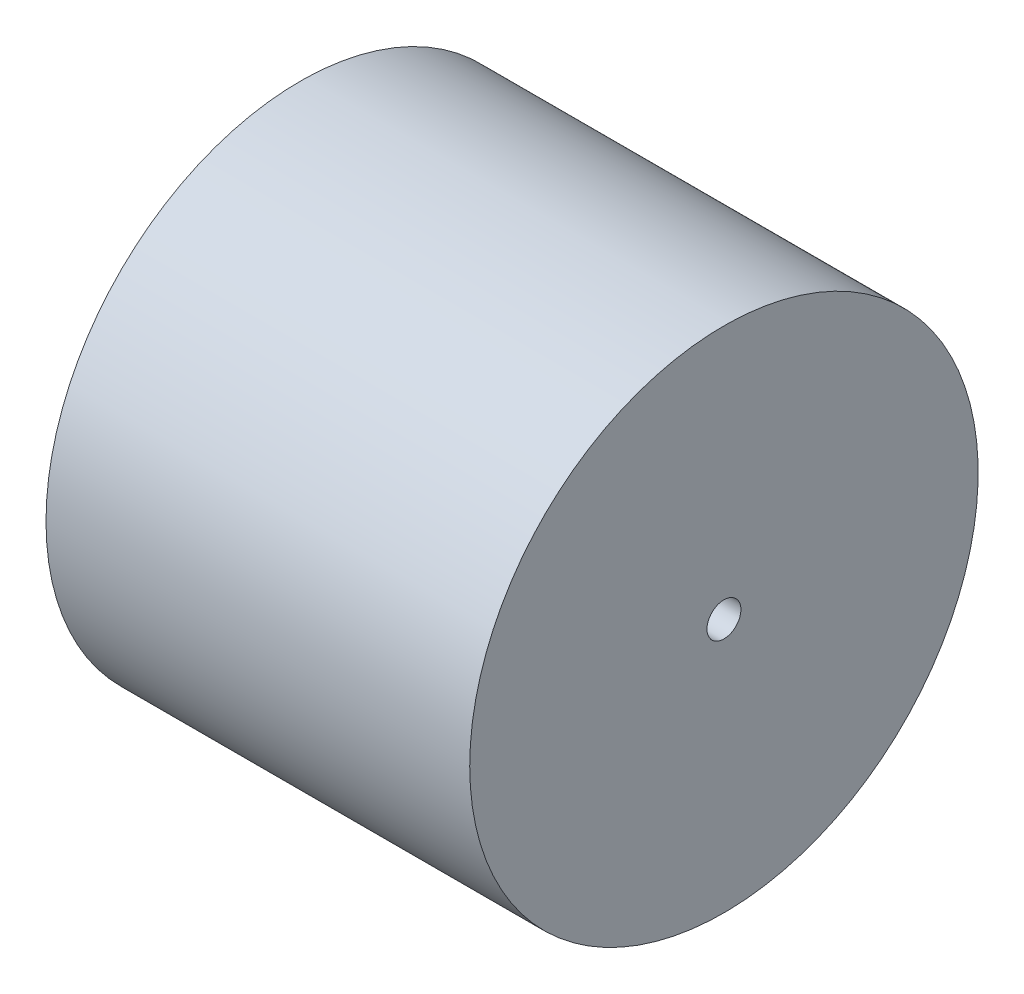
SolidWorks part; units mm, degrees
ref_plane "Front Plane" through (0, 0, 0) normal (0, 0, 1) x (1, 0, 0)
ref_plane "Top Plane" through (0, 0, 0) normal (0, 1, 0) x (1, 0, 0)
ref_plane "Right Plane" through (0, 0, 0) normal (1, 0, 0) x (0, 0, -1)
sketch "Sketch1" plane through (0, 0, 0) normal (0, 0, 1) x (1, 0, 0)
  line L0 (5, 18) -> (-25, 18)
  line L2 (5, 0) -> (5, 18)
  line L6 (-25, 18) -> (-25, 0)
  line L11 (-25, 0) -> (5, 0)
  dimension "D1" = 30
  dimension "D2" = 18
  dimension "D3" = 5
revolve "Revolve1" add sketch "Sketch1" angle 360 about L11
sketch "Sketch2" plane through (5, 0, 0) normal (1, 0, 0) x (0, 0, -1)
  circle A0 centre (0, 0) radius 1.2
  dimension "D1" = 2.4
extrude "Cut-Extrude1" cut sketch "Sketch2" against normal blind 4
sketch "Sketch3" plane through (-25, 0, 0) normal (-1, 0, 0) x (0, 0, 1)
  line L0 (-19.6498, 0) -> (29.3235, 0) construction
  circle A0 centre (0, 0) radius 3.5
  dimension "D1" = 7
extrude "Boss-Extrude1" add sketch "Sketch3" along normal blind 1.5
fillet "Fillet1" radius 0.25 1 edges at (-26.5, 0, 3.5)
sketch "Sketch4" plane through (-25, 0, 0) normal (-1, 0, 0) x (0, 0, 1)
  line L0 (-22.6728, 0) -> (22.2949, 0) construction
  circle A0 centre (-12, 0) radius 1.65
  circle A1 centre (12, 0) radius 1.65
  point P7 (0, 0)
  dimension "D1" = 3.3
  dimension "D2" = 3.3
  dimension "D3" = 12
  dimension "D4" = 12
extrude "Cut-Extrude2" cut sketch "Sketch4" against normal blind 2
